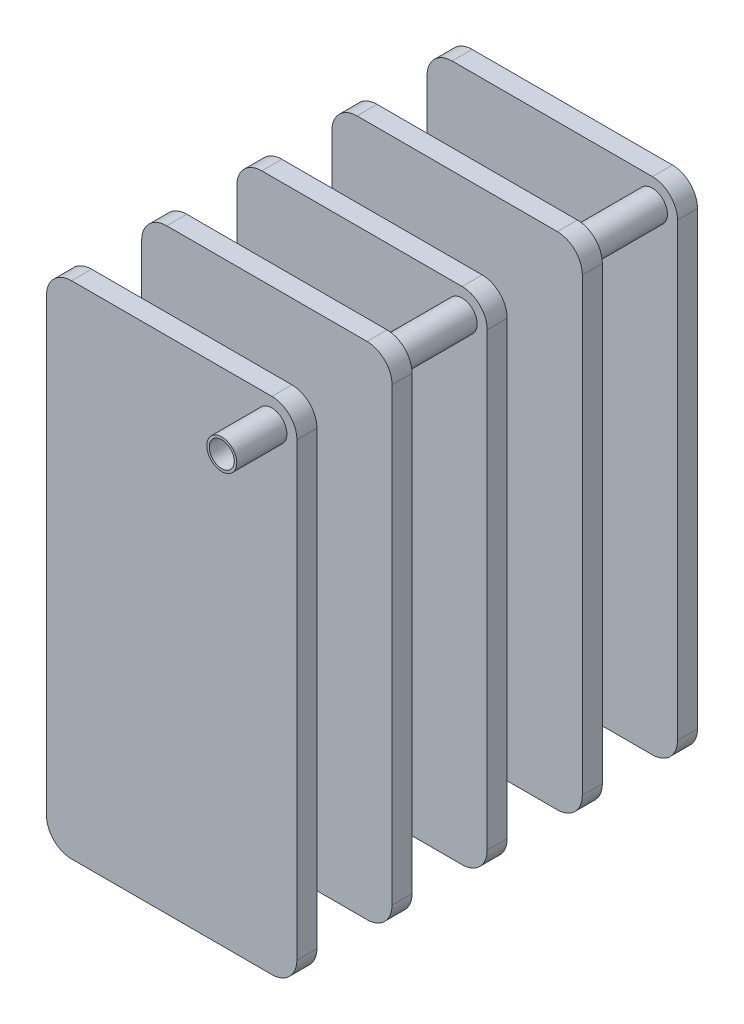
SolidWorks part; units mm, degrees
ref_plane "前视基准面" through (0, 0, 0) normal (0, 0, 1) x (1, 0, 0)
ref_plane "上视基准面" through (0, 0, 0) normal (0, 1, 0) x (1, 0, 0)
ref_plane "右视基准面" through (0, 0, 0) normal (1, 0, 0) x (0, 0, -1)
sketch "草图1" plane through (0, 0, 0) normal (0, 0, 1) x (1, 0, 0)
  line L0 (0, 0) -> (40.4315, 0) construction
  line L1 (0, 0) -> (0, -28.9035) construction
  line L3 (-25, 50) -> (25, 50)
  line L4 (-25, 50) -> (-25, -50)
  line L5 (-25, -50) -> (25, -50)
  line L6 (25, 50) -> (25, -50)
  line L7 (-25, 50) -> (25, -50) construction
  line L8 (-25, -50) -> (25, 50) construction
  point P4 (0, 0)
  dimension "D1" = 50
  dimension "D2" = 100
extrude "凸台-拉伸1" add sketch "草图1" along normal blind 4
fillet "圆角2" radius 5 1 edges at (25, 50, 2)
fillet "圆角3" radius 5 1 edges at (-25, 50, 2)
fillet "圆角4" radius 5 1 edges at (25, -50, 2)
fillet "圆角5" radius 5 1 edges at (-25, -50, 2)
sketch "草图2" plane through (0, 0, 4) normal (0, 0, 1) x (1, 0, 0)
  line L0 (20, 50) -> (-20, 50) construction
  line L1 (25, -45) -> (25, 45) construction
  circle A0 centre (20, 45) radius 3
  dimension "D1" = 5
  dimension "D2" = 6
  dimension "D3" = 5
extrude "凸台-拉伸2" add sketch "草图2" along normal blind 10 contours A0
sketch "草图3" plane through (0, 0, 0) normal (0, 0, -1) x (-1, 0, 0)
  line L0 (25, 45) -> (25, -45) construction
  line L1 (20, -50) -> (-20, -50) construction
  circle A0 centre (20, -45) radius 3
  dimension "D1" = 6
  dimension "D2" = 5
  dimension "D3" = 5
extrude "凸台-拉伸3" add sketch "草图3" along normal blind 15 contours A0
ref_plane "基准面2" through (0, 0, -15) normal (0, 0, -1) x (-1, 0, 0)
sketch "草图6" plane through (0, 0, -15) normal (0, 0, -1) x (-1, 0, 0)
  line L1 (-25, 50) -> (25, 50)
  line L2 (-25, 50) -> (-25, -50)
  line L3 (-25, -50) -> (25, -50)
  line L4 (25, 50) -> (25, -50)
  line L5 (-25, 50) -> (25, -50) construction
  line L6 (-25, -50) -> (25, 50) construction
  point P0 (0, 0)
  dimension "D1" = 50
  dimension "D2" = 100
extrude "凸台-拉伸4" add sketch "草图6" along normal blind 4
fillet "圆角6" radius 5 1 edges at (25, 50, -17)
fillet "圆角7" radius 5 1 edges at (-25, 50, -17)
fillet "圆角8" radius 5 1 edges at (-25, -50, -17)
fillet "圆角9" radius 5 1 edges at (25, -50, -17)
ref_plane "基准面3" through (0, 0, -34) normal (0, 0, -1) x (-1, 0, 0)
sketch "草图7" plane through (0, 0, -34) normal (0, 0, -1) x (-1, 0, 0)
  line L1 (-25, 50) -> (25, 50)
  line L2 (-25, 50) -> (-25, -50)
  line L3 (-25, -50) -> (25, -50)
  line L4 (25, 50) -> (25, -50)
  line L5 (-25, 50) -> (25, -50) construction
  line L6 (-25, -50) -> (25, 50) construction
  point P0 (0, 0)
  dimension "D1" = 50
  dimension "D2" = 100
extrude "凸台-拉伸5" add sketch "草图7" along normal blind 4 separate body
sketch "草图8" plane through (0, 0, -19) normal (0, 0, -1) x (-1, 0, 0)
  line L0 (20, 50) -> (-20, 50) construction
  line L1 (-25, 45) -> (-25, -45) construction
  circle A0 centre (-20, 45) radius 3
  dimension "D1" = 6
  dimension "D2" = 5
  dimension "D3" = 5
extrude "凸台-拉伸6" add sketch "草图8" along normal blind 15 contours A0
ref_plane "基准面4" through (0, 0, -53) normal (0, 0, -1) x (-1, 0, 0)
sketch "草图9" plane through (0, 0, -53) normal (0, 0, -1) x (-1, 0, 0)
  line L1 (-25, 50) -> (25, 50)
  line L2 (-25, 50) -> (-25, -50)
  line L3 (-25, -50) -> (25, -50)
  line L4 (25, 50) -> (25, -50)
  line L5 (-25, 50) -> (25, -50) construction
  line L6 (-25, -50) -> (25, 50) construction
  point P0 (0, 0)
  dimension "D1" = 50
  dimension "D2" = 100
extrude "凸台-拉伸7" add sketch "草图9" along normal blind 4 separate body
sketch "草图11" plane through (0, 0, -38) normal (0, 0, -1) x (-1, 0, 0)
  line L0 (25, -50) -> (25, 50) construction
  line L1 (-25, -50) -> (25, -50) construction
  circle A0 centre (20, -45) radius 3
  dimension "D1" = 6
  dimension "D2" = 5
  dimension "D3" = 5
extrude "凸台-拉伸9" add sketch "草图11" along normal blind 15
fillet "圆角10" radius 5 1 edges at (25, 50, -36)
fillet "圆角11" radius 5 1 edges at (25, 50, -55)
fillet "圆角12" radius 5 1 edges at (-25, 50, -55)
fillet "圆角13" radius 5 1 edges at (-25, 50, -36)
fillet "圆角14" radius 5 1 edges at (-25, -50, -55)
fillet "圆角15" radius 5 1 edges at (-25, -50, -36)
fillet "圆角16" radius 5 1 edges at (25, -50, -55)
fillet "圆角17" radius 5 1 edges at (25, -50, -36)
ref_plane "基准面5" through (0, 0, -72) normal (0, 0, -1) x (-1, 0, 0)
sketch "草图13" plane through (0, 0, -72) normal (0, 0, -1) x (-1, 0, 0)
  line L1 (-25, 50) -> (25, 50)
  line L2 (-25, 50) -> (-25, -50)
  line L3 (-25, -50) -> (25, -50)
  line L4 (25, 50) -> (25, -50)
  line L5 (-25, 50) -> (25, -50) construction
  line L6 (-25, -50) -> (25, 50) construction
  point P0 (0, 0)
  dimension "D1" = 50
  dimension "D2" = 100
extrude "凸台-拉伸10" add sketch "草图13" along normal blind 4 separate body
sketch "草图14" plane through (0, 0, -57) normal (0, 0, -1) x (-1, 0, 0)
  line L0 (20, 50) -> (-20, 50) construction
  line L1 (-25, 45) -> (-25, -45) construction
  circle A0 centre (-20, 45) radius 3
  dimension "D1" = 6
  dimension "D2" = 5
  dimension "D3" = 5
extrude "凸台-拉伸11" add sketch "草图14" along normal blind 15 contours A0
fillet "圆角18" radius 5 1 edges at (25, 50, -74)
fillet "圆角19" radius 5 1 edges at (-25, 50, -74)
fillet "圆角20" radius 5 1 edges at (25, -50, -74)
fillet "圆角21" radius 5 1 edges at (-25, -50, -74)
sketch "草图15" plane through (0, 0, -76) normal (0, 0, -1) x (-1, 0, 0)
  line L0 (-20, -50) -> (20, -50) construction
  line L1 (25, -45) -> (25, 45) construction
  circle A0 centre (20, -45) radius 3
  dimension "D1" = 6
  dimension "D2" = 5
  dimension "D3" = 5
extrude "凸台-拉伸12" add sketch "草图15" along normal blind 10
shell "抽壳1" thickness 0.5
